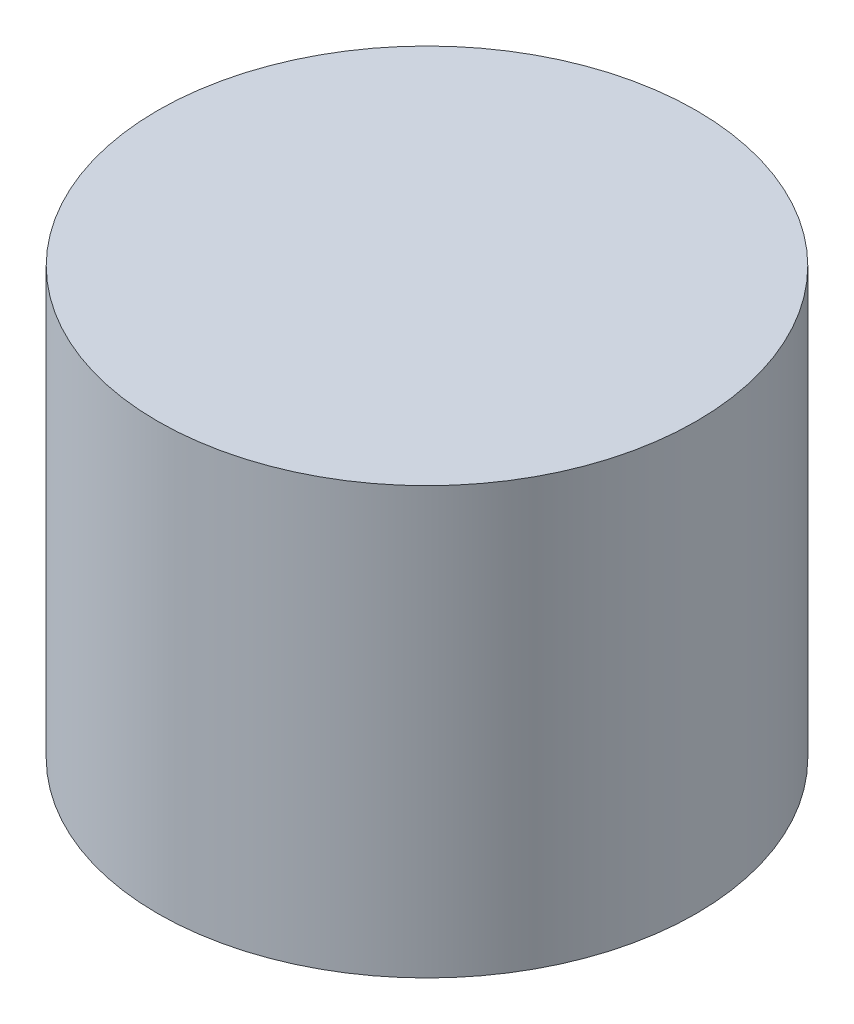
SolidWorks part; units mm, degrees
ref_plane "Front Plane" through (0, 0, 0) normal (0, 0, 1) x (1, 0, 0)
ref_plane "Top Plane" through (0, 0, 0) normal (0, 1, 0) x (1, 0, 0)
ref_plane "Right Plane" through (0, 0, 0) normal (1, 0, 0) x (0, 0, -1)
sketch "Sketch1" plane through (0, 0, 0) normal (0, 1, 0) x (1, 0, 0)
  circle A0 centre (0, 0) radius 6
extrude "Boss-Extrude1" add sketch "Sketch1" along normal blind 9.5
